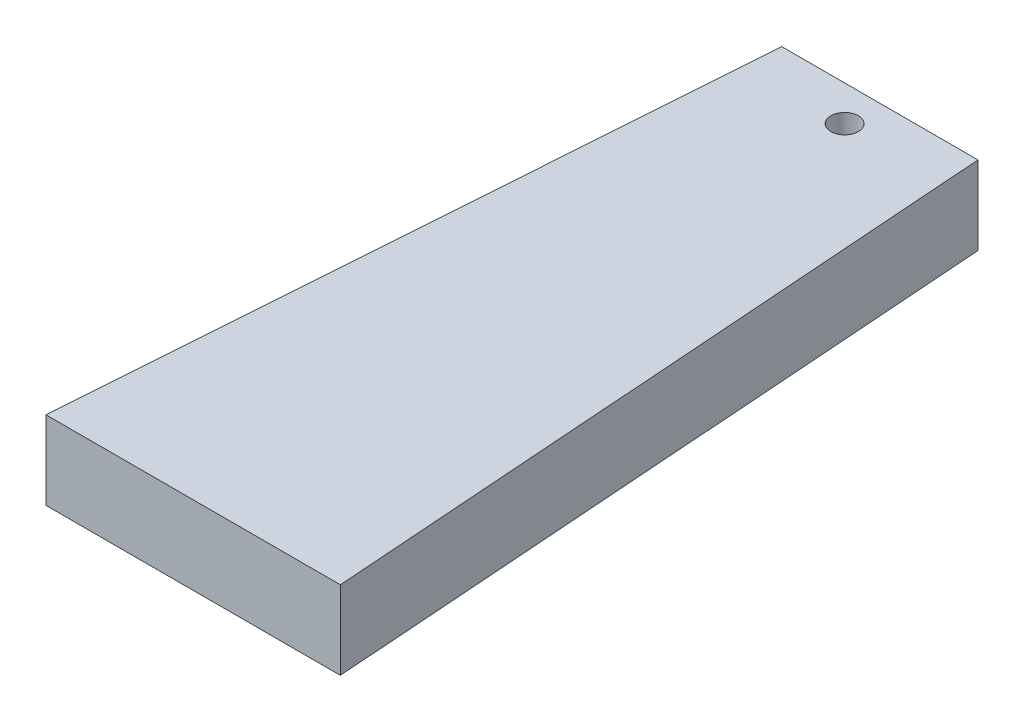
SolidWorks part; units mm, degrees
ref_plane "Front Plane" through (0, 0, 0) normal (0, 0, 1) x (1, 0, 0)
ref_plane "Top Plane" through (0, 0, 0) normal (0, 1, 0) x (1, 0, 0)
ref_plane "Right Plane" through (0, 0, 0) normal (1, 0, 0) x (0, 0, -1)
sketch "Sketch1" plane through (0, 0, 0) normal (0, 0, 1) x (1, 0, 0)
  line L1 (15, -4) -> (-15, -4)
  line L2 (15, -4) -> (15, 4)
  line L3 (15, 4) -> (-15, 4)
  line L4 (-15, -4) -> (-15, 4)
  line L5 (15, -4) -> (-15, 4) construction
  line L6 (15, 4) -> (-15, -4) construction
  point P0 (0, 0)
  dimension "D1" = 30
  dimension "D2" = 8
extrude "Boss-Extrude1" add sketch "Sketch1" along normal blind 70 contours L3 L4 L1 L2
sketch "Sketch4" plane through (0, 4, 0) normal (0, 1, 0) x (1, 0, 0)
  line L0 (-15, 0) -> (-10, 0)
  line L1 (15, 0) -> (-15, 0) construction
  line L2 (-10, 0) -> (-15, -70)
  line L3 (-15, -70) -> (-15, 0)
  line L4 (15, 0) -> (10, 0)
  line L5 (10, 0) -> (15, -70)
  line L6 (15, -70) -> (15, 0)
  dimension "D1" = 5
  dimension "D2" = 5
extrude "Cut-Extrude1" cut sketch "Sketch4" against normal blind 70
sketch "Sketch5" plane through (0, 4, 0) normal (0, 1, 0) x (1, 0, 0)
  line L0 (0, -70) -> (0, -5)
  line L1 (15, -70) -> (-15, -70) construction
  line L2 (0, -5) -> (0, -3.6)
  circle A1 centre (0, -3.6) radius 1.4
  dimension "D1" = 65
  dimension "D2" = 1.4
extrude "Cut-Extrude3" cut sketch "Sketch5" against normal blind 100 contours A1
